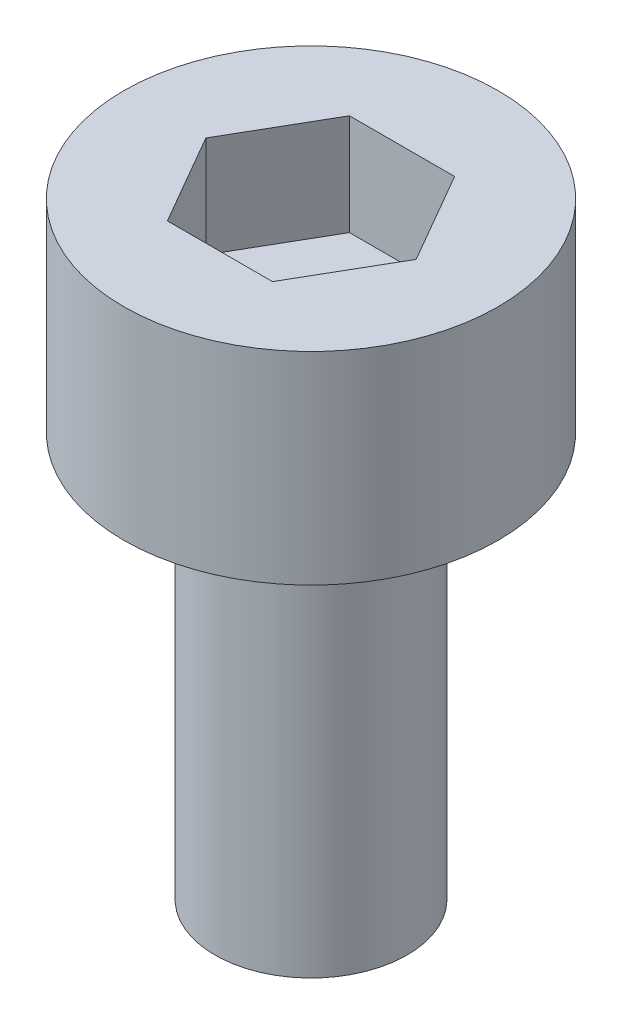
SolidWorks part; units mm, degrees
ref_plane "Front Plane" through (0, 0, 0) normal (0, 0, 1) x (1, 0, 0)
ref_plane "Top Plane" through (0, 0, 0) normal (0, 1, 0) x (1, 0, 0)
ref_plane "Right Plane" through (0, 0, 0) normal (1, 0, 0) x (0, 0, -1)
sketch "Sketch1" plane through (0, 0, 0) normal (0, 1, 0) x (1, 0, 0)
  circle A0 centre (0, 0) radius 1.85
  dimension "D1" = 3.7
extrude "Boss-Extrude1" add sketch "Sketch1" along normal blind 2
sketch "Sketch2" plane through (0, 2, 0) normal (0, 1, 0) x (1, 0, 0)
  line L1 (1.0392, 0) -> (0.5196, 0.9)
  line L2 (0.5196, 0.9) -> (-0.5196, 0.9)
  line L3 (-0.5196, 0.9) -> (-1.0392, 0)
  line L4 (-1.0392, 0) -> (-0.5196, -0.9)
  line L5 (-0.5196, -0.9) -> (0.5196, -0.9)
  line L6 (0.5196, -0.9) -> (1.0392, 0)
  circle A0 centre (0, 0) radius 0.9 construction
  dimension "D1" = 1.8
extrude "Cut-Extrude1" cut sketch "Sketch2" against normal blind 1
sketch "Sketch3" plane through (0, 0, 0) normal (0, -1, 0) x (1, 0, 0)
  circle A0 centre (0, 0) radius 0.95
  dimension "D1" = 1.9
extrude "Boss-Extrude2" add sketch "Sketch3" along normal blind 4
